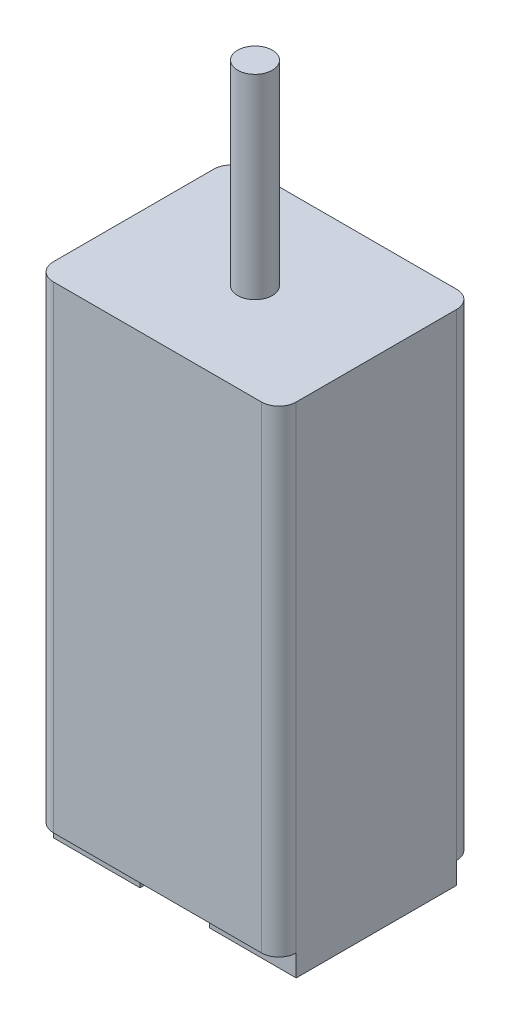
SolidWorks part; units mm, degrees
ref_plane "Front Plane" through (0, 0, 0) normal (0, 0, 1) x (1, 0, 0)
ref_plane "Top Plane" through (0, 0, 0) normal (0, 1, 0) x (1, 0, 0)
ref_plane "Right Plane" through (0, 0, 0) normal (1, 0, 0) x (0, 0, -1)
sketch "Sketch1" plane through (0, 0, 0) normal (0, 1, 0) x (1, 0, 0)
  line L1 (-2.8, 2.25) -> (2.8, 2.25)
  line L2 (-2.8, 2.25) -> (-2.8, -2.25)
  line L3 (-2.8, -2.25) -> (2.8, -2.25)
  line L4 (2.8, 2.25) -> (2.8, -2.25)
  line L5 (-2.8, 2.25) -> (2.8, -2.25) construction
  line L6 (-2.8, -2.25) -> (2.8, 2.25) construction
  point P0 (0, 0)
  dimension "D1" = 4.5
  dimension "D2" = 5.6
extrude "Boss-Extrude1" add sketch "Sketch1" along normal blind 11
sketch "Sketch2" plane through (0, 11, 0) normal (0, 1, 0) x (1, 0, 0)
  circle A0 centre (0, 0) radius 0.4
  dimension "D1" = 0.8
extrude "Boss-Extrude2" add sketch "Sketch2" along normal blind 4.5
fillet "Fillet1" radius 0.4 4 edges at (2.8, 5.5, -2.25) (-2.8, 5.5, -2.25) (-2.8, 5.5, 2.25) (2.8, 5.5, 2.25)
sketch "Sketch3" plane through (0, 0, 0) normal (0, -1, 0) x (1, 0, 0)
  line L0 (0, -2.475) -> (0, 2.475) construction
  line L1 (-2.8, 1.85) -> (-0.8, 1.85)
  line L2 (-2.8, 1.85) -> (-2.8, -1.85)
  line L3 (-2.8, -1.85) -> (-0.8, -1.85)
  line L4 (-0.8, 1.85) -> (-0.8, -0.6914)
  line L5 (2.8, -1.85) -> (0.8, -1.85)
  line L6 (2.8, 1.85) -> (2.8, -1.85)
  line L7 (0.8, 1.85) -> (0.8, -0.6914)
  line L8 (2.8, 1.85) -> (0.8, 1.85)
  arc A0 (-0.8, -1.85) -> (-0.8, -0.6914) centre (-0.9393, -1.2707) ccw
  arc A1 (0.8, -0.6914) -> (0.8, -1.85) centre (0.9967, -1.2707) ccw
  dimension "D1" = 2
extrude "Boss-Extrude3" add sketch "Sketch3" along normal blind 0.5
